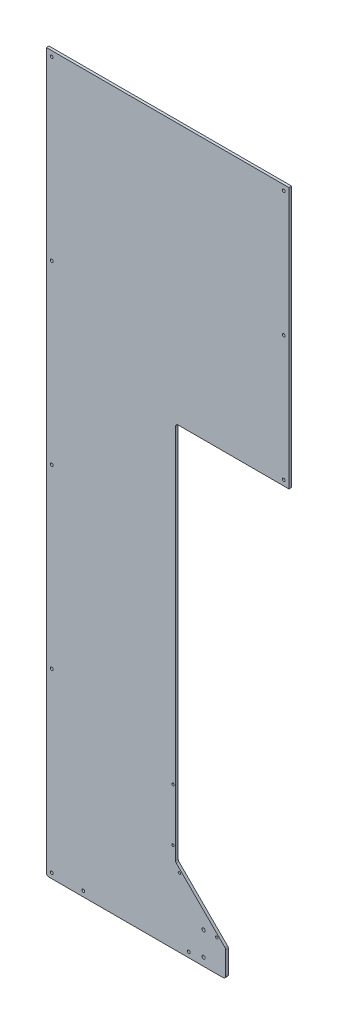
SolidWorks part; units mm, degrees
material "PC High Viscosity"
ref_plane "Front Plane" through (0, 0, 0) normal (0, 0, 1) x (1, 0, 0)
ref_plane "Top Plane" through (0, 0, 0) normal (0, 1, 0) x (1, 0, 0)
ref_plane "Right Plane" through (0, 0, 0) normal (1, 0, 0) x (0, 0, -1)
sketch "Sketch2" plane through (0, 0, 0) normal (0, 0, 1) x (1, 0, 0)
  line L1 (0, 0) -> (584.2, 0)
  line L2 (0, 0) -> (0, 1727.2)
  line L3 (0, 1727.2) -> (584.2, 1727.2)
  line L4 (584.2, 0) -> (584.2, 1727.2)
  dimension "D1" = 584.2
  dimension "D2" = 1727.2
extrude "Boss-Extrude1" add sketch "Sketch2" along normal blind 6.35
sketch "Sketch3" plane through (0, 0, 6.35) normal (0, 0, 1) x (1, 0, 0)
  line L0 (584.2, 1098.55) -> (311.15, 1098.55)
  line L1 (584.2, 0) -> (584.2, 1727.2) construction
  line L2 (311.15, 1098.55) -> (311.15, 184.15)
  line L5 (431.8, 56.7648) -> (333.3633, 155.2015) construction
  line L6 (584.2, 0) -> (431.8, 0)
  line L7 (584.2, 0) -> (584.2, 1098.55)
  line L8 (584.2, 1727.2) -> (0, 1727.2) construction
  line L9 (0, 1727.2) -> (0, 0) construction
  line L10 (311.15, 184.15) -> (431.8, 63.5)
  line L11 (431.8, 63.5) -> (431.8, 0)
  circle A0 centre (584.2, 279.4) radius 241.3 construction
  dimension "D3" = 279.4
  dimension "D5" = 482.6
  dimension "D7" = 431.8
  dimension "D1" = 628.65
  dimension "D2" = 311.15
  dimension "D4" = 584.2
  dimension "D6" = 273.05
  dimension "D8" = 63.5
  dimension "D9" = 135
  dimension "D10" = 9.525
  dimension "D11" = 56.7648
  dimension "D12" = 170.6249
extrude "Cut-Extrude1" cut sketch "Sketch3" against normal through all
sketch "Sketch4" plane through (0, 0, 6.35) normal (0, 0, 1) x (1, 0, 0)
  line L0 (0, 1727.2) -> (0, 0) construction
  line L1 (584.2, 1098.55) -> (584.2, 1727.2) construction
  line L2 (584.2, 1727.2) -> (0, 1727.2) construction
  point P0 (12.7, 1714.5)
  point P1 (12.7, 1289.05)
  point P2 (12.7, 863.6)
  point P3 (12.7, 438.15)
  point P4 (12.7, 12.7)
  point P5 (571.5, 1111.25)
  point P6 (571.5, 1412.875)
  point P7 (571.5, 1714.5)
  dimension "D1" = 12.7
  dimension "D2" = 12.7
  dimension "D3" = 12.7
  dimension "D4" = 301.625
  dimension "D5" = 603.25
  dimension "D6" = 425.45
  dimension "D7" = 425.45
  dimension "D8" = 425.45
  dimension "D9" = 425.45
hole_wizard "H (0.266) Diameter Hole1" positions "Sketch5" profile "Sketch6" hole size "H" standard "ANSI Inch" end condition through all
sketch "Sketch5" plane through (0, 0, 6.35) normal (0, 0, 1) x (1, 0, 0)
  point P0 (12.7, 1714.5)
  point P3 (12.7, 1289.05)
  point P6 (12.7, 863.6)
  point P9 (12.7, 438.15)
  point P12 (12.7, 12.7)
  point P15 (571.5, 1111.25)
  point P18 (571.5, 1412.875)
  point P21 (571.5, 1714.5)
sketch "Sketch6" plane through (12.7, 1714.5, 6.35) normal (1, 0, 0) x (0, -1, 0)
  line L0 (0, 0) -> (0, 6.35)
  line L1 (0, 6.35) -> (3.3782, 6.35)
  line L2 (3.3782, 6.35) -> (3.3782, 0)
  line L5 (3.3782, 0) -> (0, 0)
  line L11 (0, -6.35) -> (0, 107.95) construction
  dimension "Thru Hole Dia." = 6.7564
  dimension "Thru Hole Depth" = 6.35
fillet "Fillet1" radius 6.35 5 edges at (311.15, 1098.55, 3.175) (431.8, 63.5, 3.175) (311.15, 184.15, 3.175) (0, 0, 3.175) (431.8, 0, 3.175)
sketch "Sketch7" plane through (0, 0, 6.35) normal (0, 0, 1) x (1, 0, 0)
  line L0 (6.35, 0) -> (425.45, 0) construction
  line L1 (0, 1727.2) -> (0, 6.35) construction
  circle A0 centre (88.9, 12.7) radius 3.3782
  circle A1 centre (342.9, 12.7) radius 3.3782
  dimension "D1" = 12.7
  dimension "D3" = 6.7564
  dimension "D2" = 254
  dimension "D4" = 88.9
extrude "Cut-Extrude2" cut sketch "Sketch7" against normal blind 12.7
sketch "Sketch8" plane through (0, 0, 0) normal (0, 0, 1) x (1, 0, 0)
  line L0 (311.15, 1092.2) -> (311.15, 186.7803) construction
  line L1 (6.35, 0) -> (425.45, 0) construction
  circle A0 centre (304.8, 342.9) radius 3.3655 construction
  circle A1 centre (304.8, 215.9) radius 3.3655 construction
  point P5 (304.8, 342.9)
  point P8 (304.8, 215.9)
  dimension "D1" = 6.35
  dimension "D2" = 6.731
  dimension "D3" = 127
  dimension "D4" = 215.9
sketch "Sketch10" plane through (0, 0, 0) normal (0, 0, 1) x (1, 0, 0)
  line L0 (320.3172, 166.0026) -> (410.1197, 76.2) construction
  line L2 (313.0099, 182.2901) -> (429.9401, 65.3599) construction
  line L3 (6.35, 0) -> (425.45, 0) construction
  circle A0 centre (320.3172, 166.0026) radius 3.3655 construction
  circle A1 centre (410.1197, 76.2) radius 3.3655 construction
  point P9 (410.1197, 76.2)
  point P10 (320.3172, 166.0026)
  dimension "D1" = 127
  dimension "D4" = 6.731
  dimension "D2" = 76.2
  dimension "D3" = 6.35
hole_wizard "CSK for #10 Flat Head Machine Screw1" positions "Sketch13" profile "Sketch14" countersink size "#10" standard "ANSI Inch" end condition through all
sketch "Sketch13" plane through (0, 0, 0) normal (0, 0, -1) x (-1, 0, 0)
  point P0 (-304.8, 342.9)
  point P3 (-304.8, 215.9)
  point P6 (-320.3172, 166.0026)
  point P9 (-410.1197, 76.2)
sketch "Sketch14" plane through (304.8, 342.9, 0) normal (1, 0, 0) x (0, 1, 0)
  line L0 (0, 0) -> (0, 6.35)
  line L1 (0, 6.35) -> (2.8067, 6.35)
  line L2 (2.8067, 6.35) -> (2.8067, 2.396)
  line L3 (2.8067, 2.396) -> (4.8895, 0)
  line L5 (4.8895, 0) -> (0, 0)
  line L6 (-2.8067, 2.396) -> (-4.8895, 0) construction
  line L11 (0, -6.35) -> (0, 107.95) construction
  dimension "Thru Hole Dia." = 5.6134
  dimension "Thru Hole Depth" = 6.35
  dimension "Near C'Sink Dia." = 9.779
  dimension "Near C'Sink Angle" = 82
sketch "Sketch15" plane through (0, 0, 6.35) normal (0, 0, 1) x (1, 0, 0)
  line L0 (431.8, 60.8697) -> (431.8, 6.35) construction
  line L1 (6.35, 0) -> (425.45, 0) construction
  circle A0 centre (378.4676, 19.05) radius 3.937
  circle A1 centre (378.4676, 76.2) radius 3.937
  point P8 (0, 0)
  dimension "D3" = 7.874
  dimension "D1" = 53.3324
  dimension "D2" = 57.15
  dimension "D4" = 19.05
extrude "Cut-Extrude3" cut sketch "Sketch15" against normal through all
